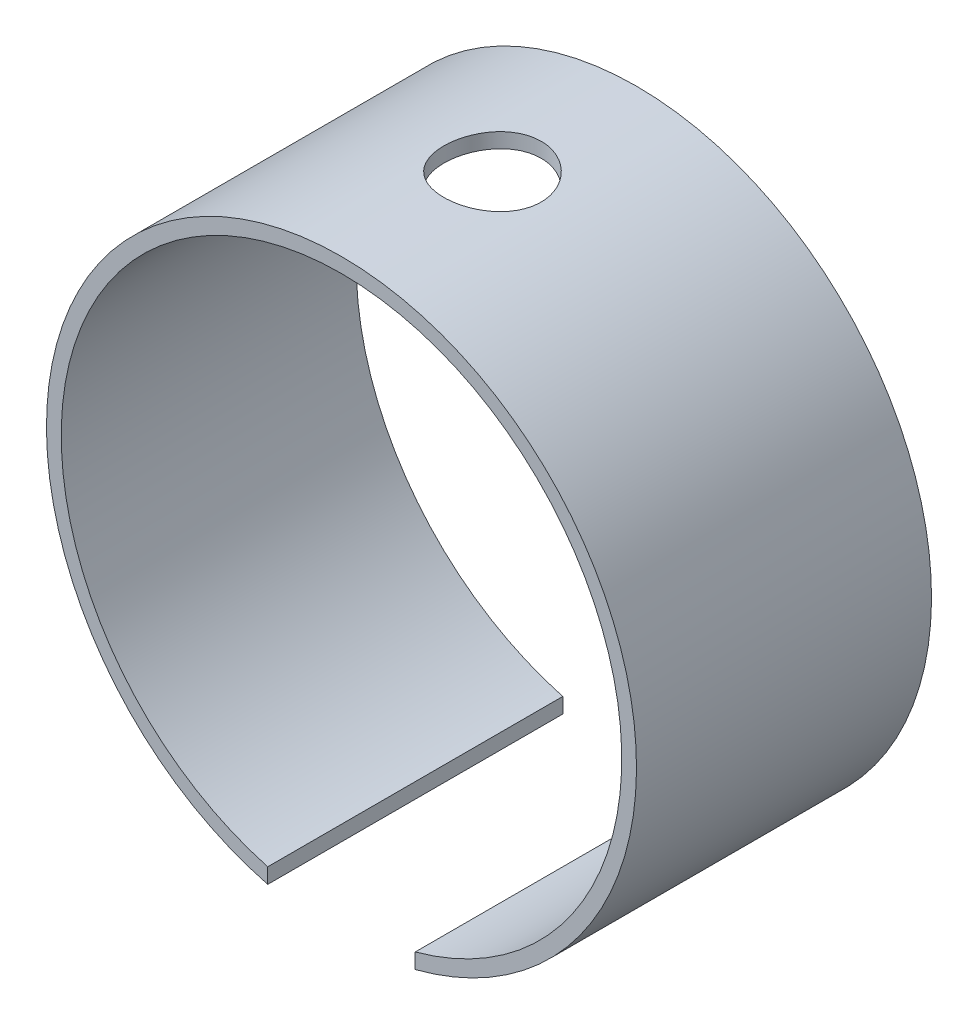
SolidWorks part; units mm, degrees
ref_plane "前视基准面" through (0, 0, 0) normal (0, 0, 1) x (1, 0, 0)
ref_plane "上视基准面" through (0, 0, 0) normal (0, 1, 0) x (1, 0, 0)
ref_plane "右视基准面" through (0, 0, 0) normal (1, 0, 0) x (0, 0, -1)
sketch "草图1" plane through (0, 0, 0) normal (0, 0, 1) x (1, 0, 0)
  circle A0 centre (0, 0) radius 10
  circle A1 centre (0, 0) radius 9.5
  dimension "D1" = 20
  dimension "19" = 19
extrude "凸台-拉伸1" add sketch "草图1" along normal blind 10
sketch "草图2" plane through (0, 0, 0) normal (0, 1, 0) x (1, 0, 0)
  circle A0 centre (0, -4.8824) radius 1.65
  dimension "3" = 3.3
extrude "切除-拉伸1" cut sketch "草图2" along normal through all
sketch "草图3" plane through (0, 0, 0) normal (0, 1, 0) x (1, 0, 0)
  line L1 (2.5, -15.2158) -> (-2.5, -15.2158)
  line L2 (2.5, -15.2158) -> (2.5, 5.451)
  line L3 (2.5, 5.451) -> (-2.5, 5.451)
  line L4 (-2.5, -15.2158) -> (-2.5, 5.451)
  line L5 (2.5, -15.2158) -> (-2.5, 5.451) construction
  line L6 (2.5, 5.451) -> (-2.5, -15.2158) construction
  point P0 (0, -4.8824)
  dimension "D1" = 5
extrude "切除-拉伸2" cut sketch "草图3" against normal through all contours L2 L1 L4 L3
